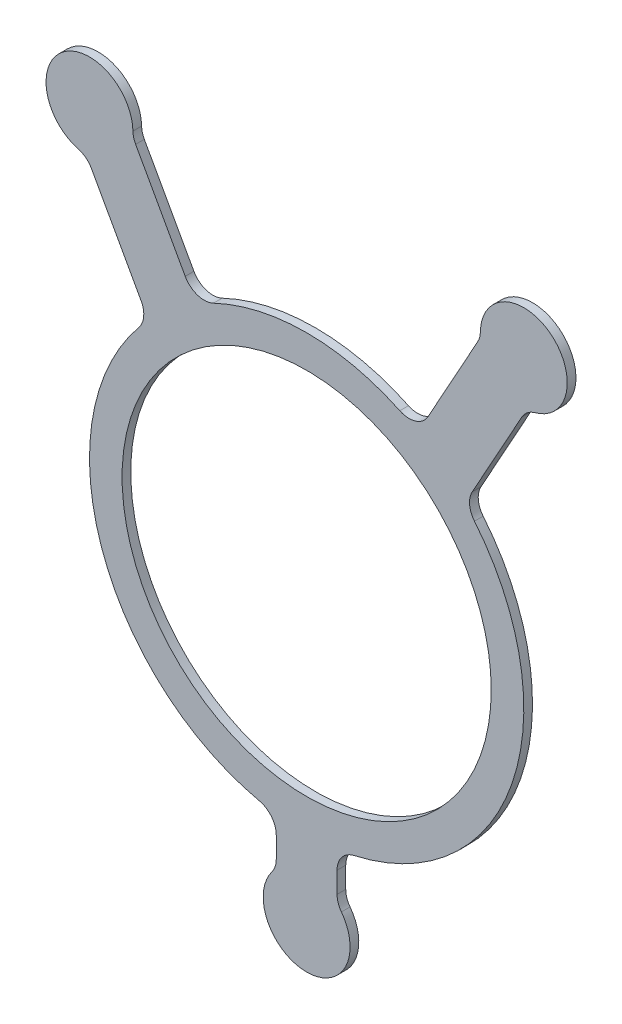
SolidWorks part; units mm, degrees
ref_plane "Front" through (0, 0, 0) normal (0, 0, 1) x (1, 0, 0)
ref_plane "Top" through (0, 0, 0) normal (0, 1, 0) x (1, 0, 0)
ref_plane "Right" through (0, 0, 0) normal (1, 0, 0) x (0, 0, -1)
other "Configuration Table"
sketch "Sketch1" plane through (0, 0, 0) normal (0, 0, 1) x (1, 0, 0)
  line L0 (0, 0) -> (0, 85.725) construction
  line L7 (50.0087, 171.9238) -> (35.5122, 145.7484)
  line L8 (62.9177, 159.3119) -> (48.4212, 133.1364)
  line L9 (-62.9177, 159.3119) -> (-48.4212, 133.1364)
  line L10 (-50.0087, 171.9238) -> (-35.5122, 145.7484)
  line L13 (8.89, 11.43) -> (8.89, 17.5578)
  line L14 (-8.89, 11.43) -> (-8.89, 17.5578)
  arc A0 (-50.8025, 174.8752) -> (-66.8151, 162.3653) centre (-63.5, 174.625) ccw
  arc A1 (50.8025, 174.8752) -> (66.8151, 162.3653) centre (63.5, 174.625) cw
  arc A2 (-10.16, 7.62) -> (10.16, 7.62) centre (0, 0) ccw
  arc A3 (-49.0693, 126.0295) -> (-13.8545, 23.7548) centre (0, 85.725) ccw
  arc A4 (27.2338, 143.0885) -> (-27.2338, 143.0885) centre (0, 85.725) ccw
  arc A5 (13.8545, 23.7548) -> (49.0693, 126.0295) centre (0, 85.725) ccw
  circle A6 centre (0, 85.725) radius 53.975
  arc A7 (-48.4212, 133.1364) -> (-49.0693, 126.0295) centre (-53.9762, 130.06) cw
  arc A8 (-27.2338, 143.0885) -> (-35.5122, 145.7484) centre (-29.9572, 148.8248) cw
  arc A9 (35.5122, 145.7484) -> (27.2338, 143.0885) centre (29.9572, 148.8248) cw
  arc A10 (49.0693, 126.0295) -> (48.4212, 133.1364) centre (53.9762, 130.06) cw
  arc A11 (8.89, 17.5578) -> (13.8545, 23.7548) centre (15.24, 17.5578) cw
  arc A12 (-13.8545, 23.7548) -> (-8.89, 17.5578) centre (-15.24, 17.5578) cw
  arc A13 (-66.8151, 162.3653) -> (-62.9177, 159.3119) centre (-68.4727, 156.2355) cw
  arc A14 (-50.0087, 171.9238) -> (-50.8025, 174.8752) centre (-44.4537, 175.0003) cw
  arc A15 (50.0087, 171.9238) -> (50.8025, 174.8752) centre (44.4537, 175.0003) ccw
  arc A16 (62.9177, 159.3119) -> (66.8151, 162.3653) centre (68.4727, 156.2355) cw
  arc A17 (10.16, 7.62) -> (8.89, 11.43) centre (15.24, 11.43) cw
  arc A18 (-8.89, 11.43) -> (-10.16, 7.62) centre (-15.24, 11.43) cw
  point P8 (0, 182.88)
  point P20 (32.4868, 140.2856)
  point P27 (8.89, 22.8504)
  dimension "D3" = 25.4
  dimension "D4" = 25.4
  dimension "D12" = 127
  dimension "D2" = 107.95
  dimension "D5" = 6.35
  dimension "D6" = 85.725
  dimension "D7" = 88.9
  dimension "D10" = 8.89
  dimension "D11" = 8.89
extrude "Base-Extrude" add sketch "Sketch1" along normal blind 2.54
